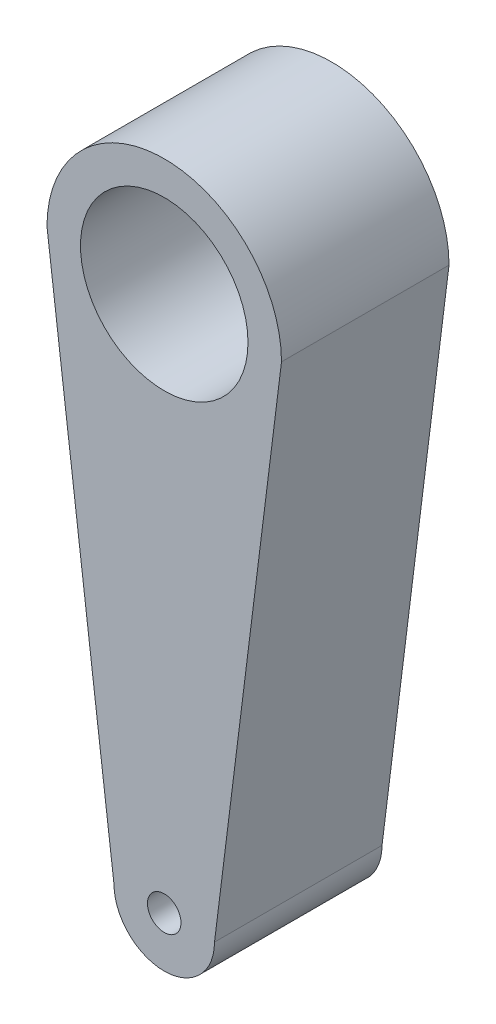
SolidWorks part; units mm, degrees
ref_plane "Alzado" through (0, 0, 0) normal (0, 0, 1) x (1, 0, 0)
ref_plane "Planta" through (0, 0, 0) normal (0, 1, 0) x (1, 0, 0)
ref_plane "Vista lateral" through (0, 0, 0) normal (1, 0, 0) x (0, 0, -1)
sketch "Croquis1" plane through (0, 0, 0) normal (0, 0, 1) x (1, 0, 0)
  line L0 (-3.5, 0) -> (-1.5, -16)
  line L1 (3.5, 0) -> (1.5, -16)
  circle A0 centre (0, 0) radius 2.5
  arc A1 (3.5, 0) -> (-3.5, 0) centre (0, 0) ccw
  circle A2 centre (0, -16) radius 0.5
  arc A3 (-1.5, -16) -> (1.5, -16) centre (0, -16) ccw
  dimension "D1" = 5
  dimension "D2" = 7
  dimension "D3" = 16
  dimension "D4" = 3
extrude "Saliente-Extruir1" add sketch "Croquis1" along normal blind 5
